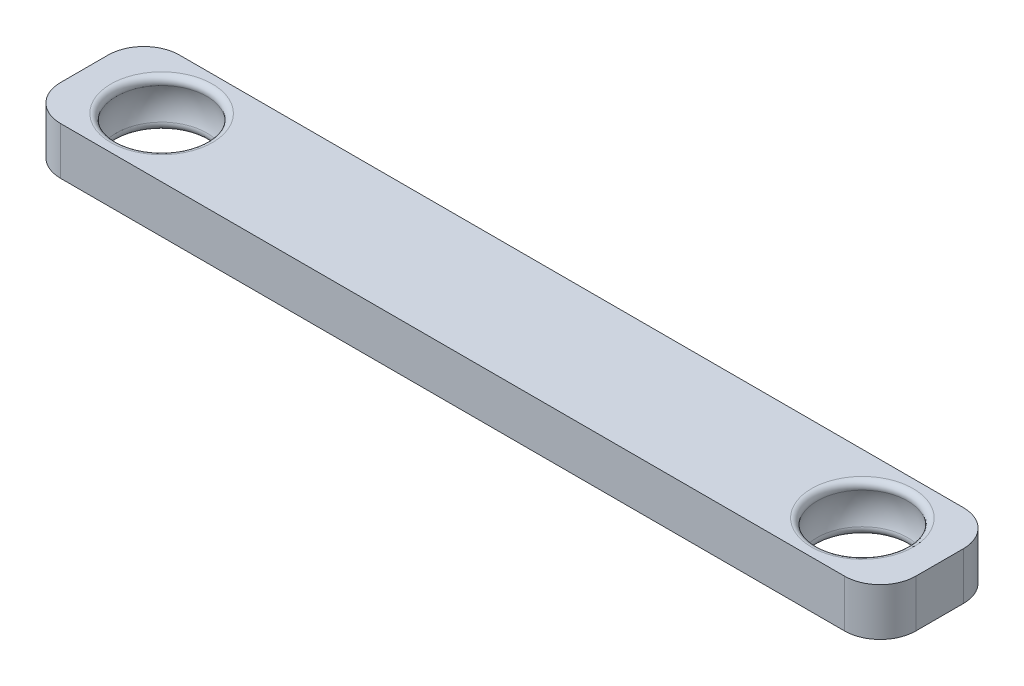
SolidWorks part; units mm, degrees
ref_plane "Front Plane" through (0, 0, 0) normal (0, 0, 1) x (1, 0, 0)
ref_plane "Top Plane" through (0, 0, 0) normal (0, 1, 0) x (1, 0, 0)
ref_plane "Right Plane" through (0, 0, 0) normal (1, 0, 0) x (0, 0, -1)
sketch "Sketch1" plane through (0, 0, 0) normal (0, 1, 0) x (1, 0, 0)
  line L1 (-36, 5) -> (36, 5)
  line L2 (-36, 5) -> (-36, -5)
  line L3 (-36, -5) -> (36, -5)
  line L4 (36, 5) -> (36, -5)
  line L5 (-36, 5) -> (36, -5) construction
  line L6 (-36, -5) -> (36, 5) construction
  point P0 (0, 0)
  dimension "D1" = 10
  dimension "D2" = 72
extrude "Boss-Extrude1" add sketch "Sketch1" along normal blind 4
sketch "Sketch2" plane through (0, 0, 0) normal (0, 0, 1) x (1, 0, 0)
  line L0 (-29.5, 4) -> (-29.5, 0)
  line L1 (-36, 4) -> (36, 4) construction
  line L2 (-36, 0) -> (36, 0) construction
  line L3 (-29.5, 4) -> (-33, 4)
  line L4 (-29.5, 0) -> (-33, 0)
  arc A0 (-33, 4) -> (-33, 0) centre (-29.5, 2) ccw
  dimension "D1" = 29.5
  dimension "D2" = 3.5
revolve "Cut-Revolve2" cut sketch "Sketch2" angle 360 about L0
fillet "Fillet1" radius 3 4 edges at (36, 2, -5) (36, 2, 5) (-36, 2, -5) (-36, 2, 5)
mirror "Mirror1" about plane through (0, 0, 0) normal (1, 0, 0) of "Cut-Revolve2"
fillet "Fillet2" radius 0.5 4 edges at (-29.5, 0, 3.5) (29.5, 0, 3.5) (29.5, 4, 3.5) (-29.5, 4, 3.5)
